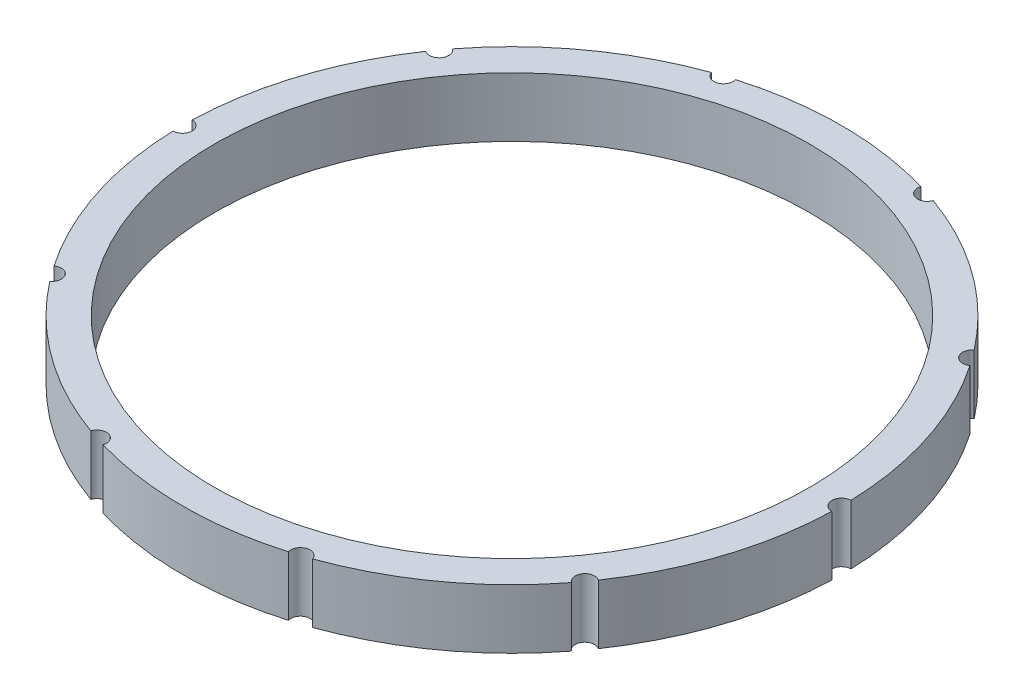
SolidWorks part; units mm, degrees
material "ABS"
ref_plane "前视基准面" through (0, 0, 0) normal (0, 0, 1) x (1, 0, 0)
ref_plane "上视基准面" through (0, 0, 0) normal (0, 1, 0) x (1, 0, 0)
ref_plane "右视基准面" through (0, 0, 0) normal (1, 0, 0) x (0, 0, -1)
sketch "草图1" plane through (0, 0, 0) normal (0, 1, 0) x (1, 0, 0)
  circle A0 centre (0, 0) radius 72.1
  circle A1 centre (0, 0) radius 65.1
  dimension "D1" = 130.2
  dimension "D2" = 7
extrude "凸台-拉伸1" add sketch "草图1" along normal blind 13
sketch "草图2" plane through (0, 13, 0) normal (0, 1, 0) x (1, 0, 0)
  circle A0 centre (0, 0) radius 72.1
  circle A1 centre (-72.1, 0) radius 2.1
  circle M1 centre (0, 0) radius 72.1
  dimension "D1" = 4.2
extrude "切除-拉伸1" cut sketch "草图2" against normal blind 13 contours A1 M1
pattern_circular "阵列(圆周)1" count 10 over 360 about axis through (0, 0, 0) along (0, 1, 0) of "切除-拉伸1"
